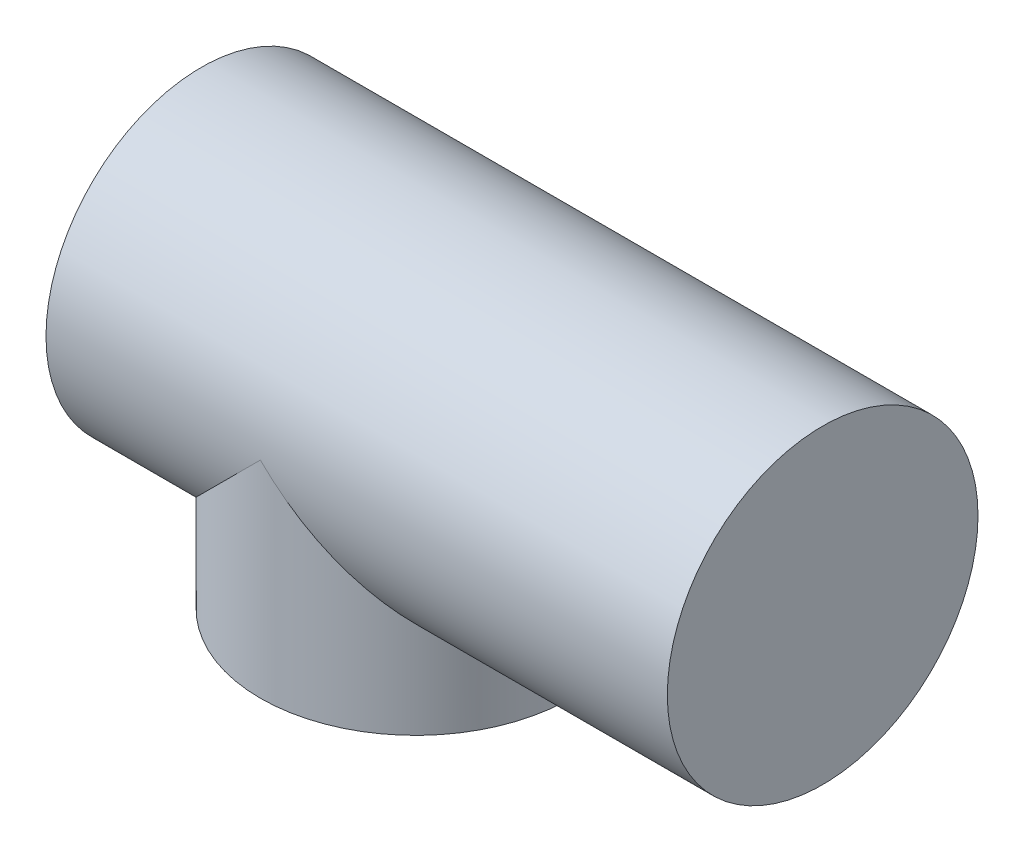
SolidWorks part; units mm, degrees
ref_plane "Front Plane" through (0, 0, 0) normal (0, 0, 1) x (1, 0, 0)
ref_plane "Top Plane" through (0, 0, 0) normal (0, 1, 0) x (1, 0, 0)
ref_plane "Right Plane" through (0, 0, 0) normal (1, 0, 0) x (0, 0, -1)
sketch "Sketch1" plane through (0, 0, 0) normal (0, 0, 1) x (1, 0, 0)
  line L0 (0, 0) -> (100, 0)
  dimension "D1" = 100
sketch "Sketch2" plane through (0, 0, 0) normal (1, 0, 0) x (0, 0, -1)
  circle A0 centre (0, 0) radius 25
  dimension "D1" = 50
sweep "Sweep1" add profiles "Sketch2" path "Sketch1"
sketch "Sketch4" plane through (0, 0, 0) normal (0, 1, 0) x (1, 0, 0)
  line L0 (0, 0) -> (100, 0) construction
  line L1 (100, -25) -> (100, 25) construction
  line L2 (0, -25) -> (100, -25) construction
  line L3 (100, 25) -> (0, 25) construction
  circle A0 centre (34.5, 0) radius 25
  point P9 (0, 0)
  dimension "D1" = 65.5
extrude "Boss-Extrude1" add sketch "Sketch4" against normal blind 33.2
